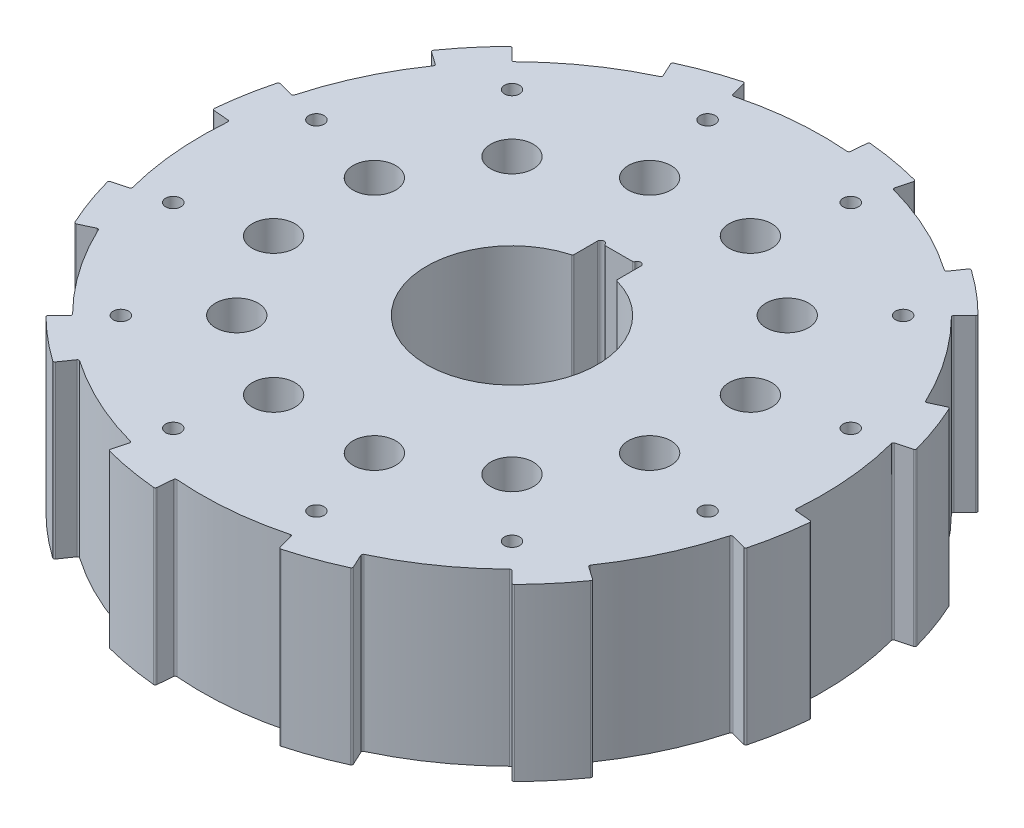
SolidWorks part; units mm, degrees
ref_plane "Front Plane" through (0, 0, 0) normal (0, 0, 1) x (1, 0, 0)
ref_plane "Top Plane" through (0, 0, 0) normal (0, 1, 0) x (1, 0, 0)
ref_plane "Right Plane" through (0, 0, 0) normal (1, 0, 0) x (0, 0, -1)
sketch "Sketch1" plane through (0, 0, 0) normal (0, 1, 0) x (1, 0, 0)
  line L0 (4.0511, 46.3044) -> (4.2504, 48.5818)
  line L1 (12.0303, 44.8975) -> (12.6219, 47.1056)
  line L2 (26.6606, 38.0753) -> (27.9718, 39.9479)
  line L3 (32.8673, 32.8673) -> (34.4837, 34.4837)
  line L4 (42.1264, 19.6438) -> (44.1982, 20.61)
  line L5 (44.8975, 12.0303) -> (47.1056, 12.6219)
  line L6 (46.3044, -4.0511) -> (48.5818, -4.2504)
  line L7 (44.8975, -12.0303) -> (47.1056, -12.6219)
  line L8 (38.0753, -26.6606) -> (39.9479, -27.9718)
  line L9 (32.8673, -32.8673) -> (34.4837, -34.4837)
  line L10 (19.6438, -42.1264) -> (20.61, -44.1982)
  line L11 (12.0303, -44.8975) -> (12.6219, -47.1056)
  line L12 (-4.0511, -46.3044) -> (-4.2504, -48.5818)
  line L13 (-12.0303, -44.8975) -> (-12.6219, -47.1056)
  line L14 (-26.6606, -38.0753) -> (-27.9718, -39.9479)
  line L15 (-32.8673, -32.8673) -> (-34.4837, -34.4837)
  line L16 (-42.1264, -19.6438) -> (-44.1982, -20.61)
  line L17 (-44.8975, -12.0303) -> (-47.1056, -12.6219)
  line L18 (-46.3044, 4.0511) -> (-48.5818, 4.2504)
  line L19 (-44.8975, 12.0303) -> (-47.1056, 12.6219)
  line L20 (-19.6438, 42.1264) -> (-20.61, 44.1982)
  line L21 (-12.0303, 44.8975) -> (-12.6219, 47.1056)
  line L22 (-38.0753, 26.6606) -> (-39.9479, 27.9718)
  line L23 (-32.8673, 32.8673) -> (-34.4837, 34.4837)
  line L24 (3.2258, 12.4779) -> (3.2258, 15.9258)
  line L25 (1.9994, 15.9258) -> (-1.9994, 15.9258)
  line L26 (-3.2258, 15.9258) -> (-3.2258, 12.4779)
  line L27 (0, 0) -> (-50000, 0) construction
  line L28 (0, 0) -> (0, 50000) construction
  arc A0 (4.5268, 48.8125) -> (4.2504, 48.5818) centre (4.5034, 48.5596) ccw
  arc A1 (12.441, 47.4171) -> (4.5268, 48.8125) centre (0, 0) ccw
  arc A2 (26.308, 38.0121) -> (12.2085, 44.5868) centre (0, 0) ccw
  arc A3 (12.6219, 47.1056) -> (12.441, 47.4171) centre (12.3766, 47.1714) ccw
  arc A4 (12.2085, 44.5868) -> (12.0303, 44.8975) centre (12.2756, 44.8318) cw
  arc A5 (4.0511, 46.3044) -> (3.7773, 46.0734) centre (3.7981, 46.3266) cw
  arc A6 (28.3266, 40.0095) -> (27.9718, 39.9479) centre (28.1799, 39.8022) ccw
  arc A7 (34.4828, 34.8439) -> (28.3266, 40.0095) centre (0, 0) ccw
  arc A8 (41.7894, 19.7654) -> (32.8663, 32.509) centre (0, 0) ccw
  arc A9 (34.4837, 34.4837) -> (34.4828, 34.8439) centre (34.3041, 34.6633) ccw
  arc A10 (32.8663, 32.509) -> (32.8673, 32.8673) centre (33.0469, 32.6876) cw
  arc A11 (26.6606, 38.0753) -> (26.308, 38.0121) centre (26.4525, 38.2209) cw
  arc A12 (44.5363, 20.4859) -> (44.1982, 20.61) centre (44.3056, 20.3798) ccw
  arc A13 (47.2849, 12.9343) -> (44.5363, 20.4859) centre (0, 0) ccw
  arc A14 (46.0734, -3.7773) -> (44.7175, 11.7205) centre (0, 0) ccw
  arc A15 (47.1056, 12.6219) -> (47.2849, 12.9343) centre (47.0399, 12.8673) ccw
  arc A16 (44.7175, 11.7205) -> (44.8975, 12.0303) centre (44.9633, 11.7849) cw
  arc A17 (42.1264, 19.6438) -> (41.7894, 19.7654) centre (42.019, 19.8741) cw
  arc A18 (48.8125, -4.5268) -> (48.5818, -4.2504) centre (48.5596, -4.5034) ccw
  arc A19 (47.4171, -12.441) -> (48.8125, -4.5268) centre (0, 0) ccw
  arc A20 (38.0121, -26.308) -> (44.5868, -12.2085) centre (0, 0) ccw
  arc A21 (47.1056, -12.6219) -> (47.4171, -12.441) centre (47.1714, -12.3766) ccw
  arc A22 (44.5868, -12.2085) -> (44.8975, -12.0303) centre (44.8318, -12.2756) cw
  arc A23 (46.3044, -4.0511) -> (46.0734, -3.7773) centre (46.3266, -3.7981) cw
  arc A24 (40.0095, -28.3266) -> (39.9479, -27.9718) centre (39.8022, -28.1799) ccw
  arc A25 (34.8439, -34.4828) -> (40.0095, -28.3266) centre (0, 0) ccw
  arc A26 (19.7654, -41.7894) -> (32.509, -32.8663) centre (0, 0) ccw
  arc A27 (34.4837, -34.4837) -> (34.8439, -34.4828) centre (34.6633, -34.3041) ccw
  arc A28 (32.509, -32.8663) -> (32.8673, -32.8673) centre (32.6876, -33.0469) cw
  arc A29 (38.0753, -26.6606) -> (38.0121, -26.308) centre (38.2209, -26.4525) cw
  arc A30 (20.4859, -44.5363) -> (20.61, -44.1982) centre (20.3798, -44.3056) ccw
  arc A31 (12.9343, -47.2849) -> (20.4859, -44.5363) centre (0, 0) ccw
  arc A32 (-3.7773, -46.0734) -> (11.7205, -44.7175) centre (0, 0) ccw
  arc A33 (12.6219, -47.1056) -> (12.9343, -47.2849) centre (12.8673, -47.0399) ccw
  arc A34 (11.7205, -44.7175) -> (12.0303, -44.8975) centre (11.7849, -44.9633) cw
  arc A35 (19.6438, -42.1264) -> (19.7654, -41.7894) centre (19.8741, -42.019) cw
  arc A36 (-4.5268, -48.8125) -> (-4.2504, -48.5818) centre (-4.5034, -48.5596) ccw
  arc A37 (-12.441, -47.4171) -> (-4.5268, -48.8125) centre (0, 0) ccw
  arc A38 (-26.308, -38.0121) -> (-12.2085, -44.5868) centre (0, 0) ccw
  arc A39 (-12.6219, -47.1056) -> (-12.441, -47.4171) centre (-12.3766, -47.1714) ccw
  arc A40 (-12.2085, -44.5868) -> (-12.0303, -44.8975) centre (-12.2756, -44.8318) cw
  arc A41 (-4.0511, -46.3044) -> (-3.7773, -46.0734) centre (-3.7981, -46.3266) cw
  arc A42 (-28.3266, -40.0095) -> (-27.9718, -39.9479) centre (-28.1799, -39.8022) ccw
  arc A43 (-34.4828, -34.8439) -> (-28.3266, -40.0095) centre (0, 0) ccw
  arc A44 (-41.7894, -19.7654) -> (-32.8663, -32.509) centre (0, 0) ccw
  arc A45 (-34.4837, -34.4837) -> (-34.4828, -34.8439) centre (-34.3041, -34.6633) ccw
  arc A46 (-32.8663, -32.509) -> (-32.8673, -32.8673) centre (-33.0469, -32.6876) cw
  arc A47 (-26.6606, -38.0753) -> (-26.308, -38.0121) centre (-26.4525, -38.2209) cw
  arc A48 (-44.5363, -20.4859) -> (-44.1982, -20.61) centre (-44.3056, -20.3798) ccw
  arc A49 (-47.2849, -12.9343) -> (-44.5363, -20.4859) centre (0, 0) ccw
  arc A50 (-46.0734, 3.7773) -> (-44.7175, -11.7205) centre (0, 0) ccw
  arc A51 (-47.1056, -12.6219) -> (-47.2849, -12.9343) centre (-47.0399, -12.8673) ccw
  arc A52 (-44.7175, -11.7205) -> (-44.8975, -12.0303) centre (-44.9633, -11.7849) cw
  arc A53 (-42.1264, -19.6438) -> (-41.7894, -19.7654) centre (-42.019, -19.8741) cw
  arc A54 (-48.8125, 4.5268) -> (-48.5818, 4.2504) centre (-48.5596, 4.5034) ccw
  arc A55 (-47.4171, 12.441) -> (-48.8125, 4.5268) centre (0, 0) ccw
  arc A56 (-38.0121, 26.308) -> (-44.5868, 12.2085) centre (0, 0) ccw
  arc A57 (-47.1056, 12.6219) -> (-47.4171, 12.441) centre (-47.1714, 12.3766) ccw
  arc A58 (-44.5868, 12.2085) -> (-44.8975, 12.0303) centre (-44.8318, 12.2756) cw
  arc A59 (-46.3044, 4.0511) -> (-46.0734, 3.7773) centre (-46.3266, 3.7981) cw
  arc A60 (-20.4859, 44.5363) -> (-20.61, 44.1982) centre (-20.3798, 44.3056) ccw
  arc A61 (-12.9343, 47.2849) -> (-20.4859, 44.5363) centre (0, 0) ccw
  arc A62 (3.7773, 46.0734) -> (-11.7205, 44.7175) centre (0, 0) ccw
  arc A63 (-12.6219, 47.1056) -> (-12.9343, 47.2849) centre (-12.8673, 47.0399) ccw
  arc A64 (-40.0095, 28.3266) -> (-39.9479, 27.9718) centre (-39.8022, 28.1799) ccw
  arc A65 (-34.8439, 34.4828) -> (-40.0095, 28.3266) centre (0, 0) ccw
  arc A66 (-3.4116, 12.2332) -> (3.4116, 12.2332) centre (0, 0) ccw
  circle A67 centre (7.4944, 27.9693) radius 3.175
  circle A68 centre (20.475, 20.475) radius 3.175
  circle A69 centre (27.9693, 7.4944) radius 3.175
  circle A70 centre (27.9693, -7.4944) radius 3.175
  circle A71 centre (20.475, -20.475) radius 3.175
  circle A72 centre (7.4944, -27.9693) radius 3.175
  circle A73 centre (-7.4944, -27.9693) radius 3.175
  circle A74 centre (-20.475, -20.475) radius 3.175
  circle A75 centre (-27.9693, -7.4944) radius 3.175
  circle A76 centre (-27.9693, 7.4944) radius 3.175
  circle A77 centre (-20.475, 20.475) radius 3.175
  circle A78 centre (-7.4944, 27.9693) radius 3.175
  circle A79 centre (10.6499, 39.7459) radius 1.1303
  circle A80 centre (29.096, 29.096) radius 1.1303
  circle A81 centre (39.7459, 10.6499) radius 1.1303
  circle A82 centre (39.7459, -10.6499) radius 1.1303
  circle A83 centre (29.096, -29.096) radius 1.1303
  circle A84 centre (10.6499, -39.7459) radius 1.1303
  circle A85 centre (-10.6499, -39.7459) radius 1.1303
  circle A86 centre (-29.096, -29.096) radius 1.1303
  circle A87 centre (-39.7459, -10.6499) radius 1.1303
  circle A88 centre (-39.7459, 10.6499) radius 1.1303
  circle A89 centre (-29.096, 29.096) radius 1.1303
  arc A91 (-1.9994, 15.9258) -> (-2.2389, 16.0951) centre (-1.9994, 16.1798) cw
  arc A92 (-2.2389, 16.0951) -> (-3.2258, 15.9258) centre (-2.7178, 15.9258) ccw
  arc A93 (2.2389, 16.0951) -> (3.2258, 15.9258) centre (2.7178, 15.9258) cw
  arc A94 (1.9994, 15.9258) -> (2.2389, 16.0951) centre (1.9994, 16.1798) ccw
  arc A95 (3.4116, 12.2332) -> (3.2258, 12.4779) centre (3.4798, 12.4779) cw
  arc A96 (-3.4116, 12.2332) -> (-3.2258, 12.4779) centre (-3.4798, 12.4779) ccw
  arc A97 (-19.7654, 41.7894) -> (-32.509, 32.8663) centre (0, 0) ccw
  arc A98 (-11.7205, 44.7175) -> (-12.0303, 44.8975) centre (-11.7849, 44.9633) cw
  arc A99 (-19.6438, 42.1264) -> (-19.7654, 41.7894) centre (-19.8741, 42.019) cw
  arc A100 (-34.4837, 34.4837) -> (-34.8439, 34.4828) centre (-34.6633, 34.3041) ccw
  arc A101 (-32.509, 32.8663) -> (-32.8673, 32.8673) centre (-32.6876, 33.0469) cw
  arc A102 (-38.0753, 26.6606) -> (-38.0121, 26.308) centre (-38.2209, 26.4525) cw
  circle A103 centre (-10.6499, 39.7459) radius 1.1303
  point P150 (0, 0)
  point P168 (0, 0)
  point P186 (0, 0)
  point P193 (0, 0)
  point P227 (0, 0)
  dimension "D1" = 12
  dimension "D2" = 12
  dimension "D3" = 12
  dimension "D4" = 46.228
  dimension "D5" = 49.022
  dimension "D6" = 0.254
  dimension "D7" = 2.286
  dimension "D8" = 12.7
  dimension "D9" = 0.508
  dimension "D10" = 0.254
  dimension "D12" = 0.254
  dimension "D15" = 6.35
  dimension "D16" = 2.2606
  dimension "D11" = 3.4479
  dimension "D13" = 6.4516
  dimension "D14" = 28.956
  dimension "D17" = 41.148
  dimension "D18" = 3.4479
extrude "Boss-Extrude2" add sketch "Sketch1" along normal blind 25.4
